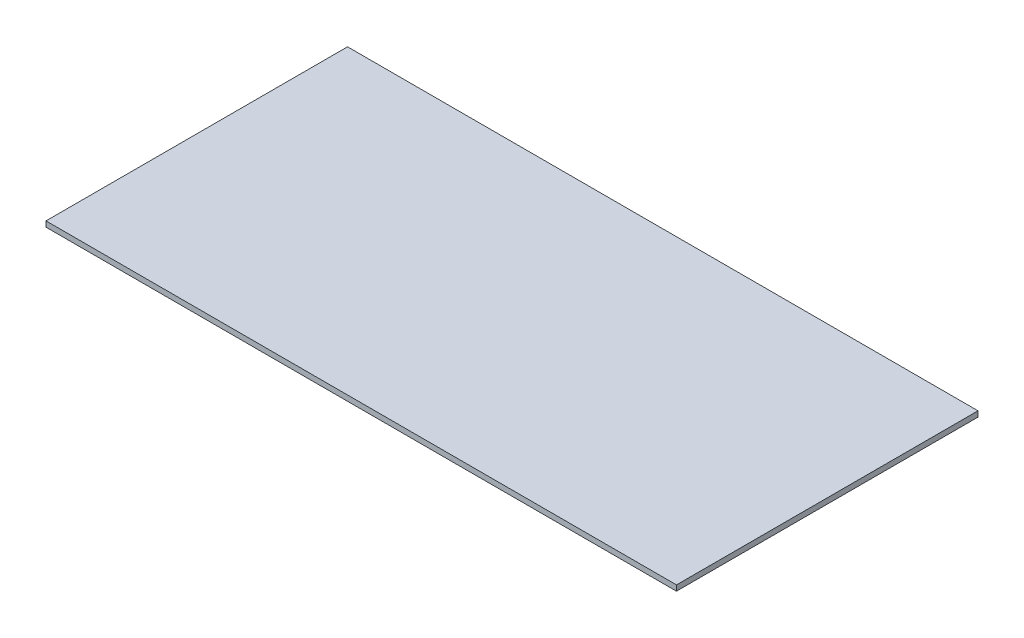
SolidWorks part; units mm, degrees
material "PC High Viscosity"
ref_plane "Front Plane" through (0, 0, 0) normal (0, 0, 1) x (1, 0, 0)
ref_plane "Top Plane" through (0, 0, 0) normal (0, 1, 0) x (1, 0, 0)
ref_plane "Right Plane" through (0, 0, 0) normal (1, 0, 0) x (0, 0, -1)
sketch "Sketch1" plane through (0, 0, 0) normal (0, 1, 0) x (1, 0, 0)
  line L1 (0, 0) -> (584.2, 0)
  line L2 (0, 0) -> (0, 279.4)
  line L3 (0, 279.4) -> (584.2, 279.4)
  line L4 (584.2, 0) -> (584.2, 279.4)
  dimension "D1" = 584.2
  dimension "D2" = 279.4
extrude "Boss-Extrude1" add sketch "Sketch1" along normal blind 5.08
sketch "Sketch2" plane through (0, 5.08, 0) normal (0, 1, 0) x (1, 0, 0)
  line L0 (0, 279.4) -> (0, 0) construction
  circle A0 centre (12.7, 262.5514) radius 7.5705
  dimension "D1" = 12.7
